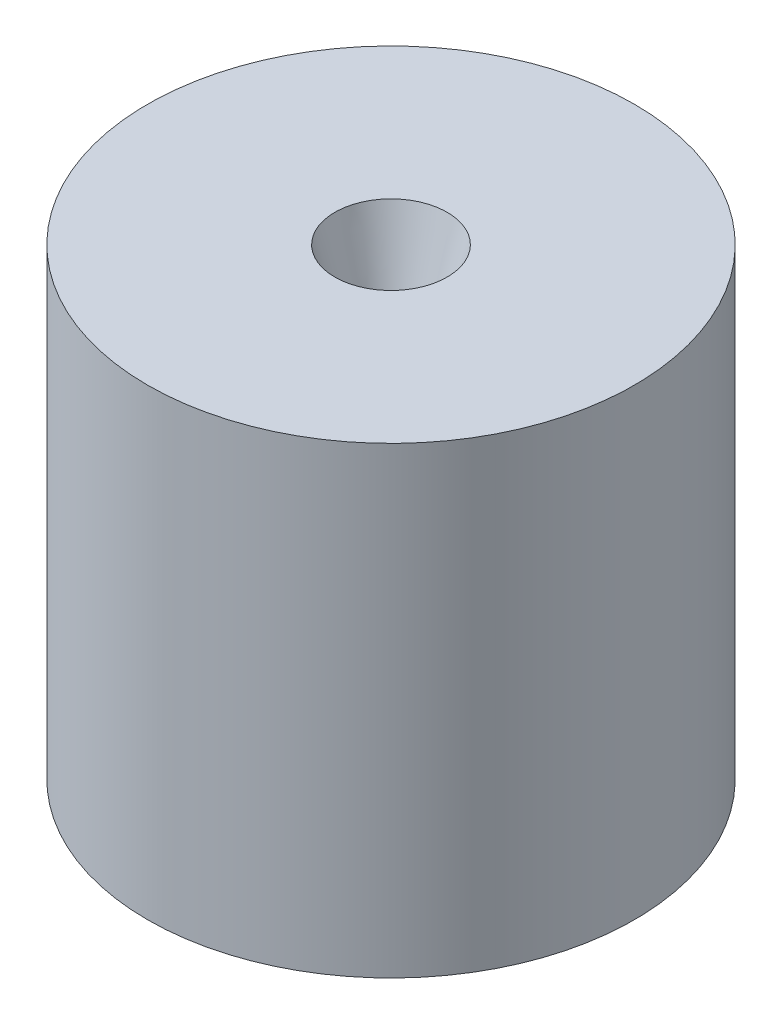
SolidWorks part; units mm, degrees
ref_plane "Front Plane" through (0, 0, 0) normal (0, 0, 1) x (1, 0, 0)
ref_plane "Top Plane" through (0, 0, 0) normal (0, 1, 0) x (1, 0, 0)
ref_plane "Right Plane" through (0, 0, 0) normal (1, 0, 0) x (0, 0, -1)
sketch "Sketch1" plane through (0, 0, 0) normal (0, 0, 1) x (1, 0, 0)
  line L0 (0, 20.7983) -> (0, -18.4168) construction
  line L1 (-12.7012, 0) -> (16.591, 0) construction
  line L2 (-1, 19.6081) -> (-1, -19.1307) construction
  line L3 (-1, 2.5) -> (-1, -2.5)
  line L4 (-1, -2.5) -> (-6.5, -8)
  line L5 (-6.5, 20.7983) -> (-6.5, -18.4168) construction
  line L6 (-1, 2.5) -> (-1.5, 4.366)
  line L7 (-1.5, 4.366) -> (-6.5, 4.366)
  line L8 (-6.5, 4.366) -> (-6.5, -8)
  point P10 (-1, 0)
  dimension "D1" = 5
  dimension "D2" = 6.5
  dimension "D3" = 15
  dimension "D4" = 1
  dimension "D5" = 1.5
  dimension "D6" = 45
revolve "Revolve1" add sketch "Sketch1" angle 360 about L0
